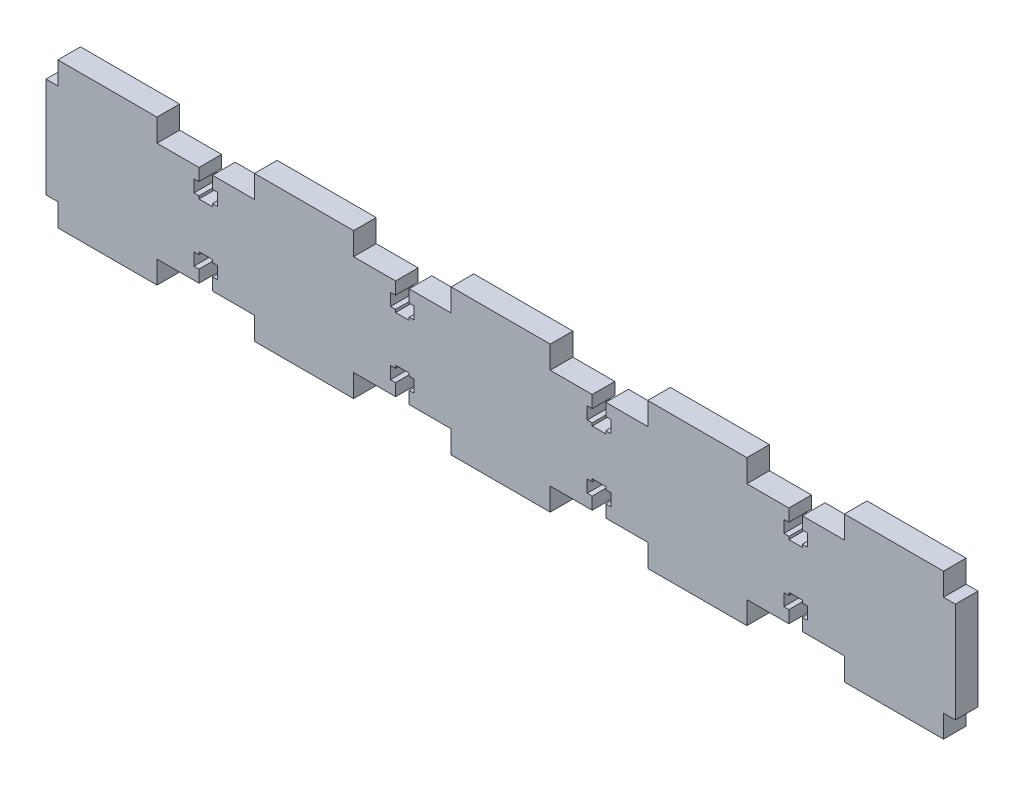
SolidWorks part; units mm, degrees
ref_plane "Front Plane" through (0, 0, 0) normal (0, 0, 1) x (1, 0, 0)
ref_plane "Top Plane" through (0, 0, 0) normal (0, 1, 0) x (1, 0, 0)
ref_plane "Right Plane" through (0, 0, 0) normal (1, 0, 0) x (0, 0, -1)
sketch "Sketch1" plane through (0, 0, 0) normal (0, 0, 1) x (1, 0, 0)
  line L0 (-38, 18.796) -> (-63.6, 18.796)
  line L1 (117.475, -12.954) -> (114.4, -12.954)
  line L2 (117.475, -12.954) -> (117.475, 12.954)
  line L3 (117.475, 12.954) -> (114.4, 12.954)
  line L4 (-117.475, -12.954) -> (-117.475, 12.954)
  line L5 (117.475, -12.954) -> (-117.475, 12.954) construction
  line L6 (117.475, 12.954) -> (-117.475, -12.954) construction
  line L7 (-88.8, 18.796) -> (-114.4, 18.796)
  line L8 (-88.8, 18.796) -> (-88.8, 12.954)
  line L9 (-63.6, 12.954) -> (-74.4474, 12.954)
  line L10 (-114.4, 18.796) -> (-114.4, 12.954)
  line L11 (-88.8, 18.796) -> (-114.4, 12.954) construction
  line L12 (-88.8, 12.954) -> (-114.4, 18.796) construction
  line L13 (-63.6, 18.796) -> (-63.6, 12.954)
  line L14 (-38, 18.796) -> (-38, 12.954)
  line L15 (12.8, 18.796) -> (-12.8, 18.796)
  line L16 (-12.8, 18.796) -> (-12.8, 12.954)
  line L17 (12.8, 18.796) -> (12.8, 12.954)
  line L18 (63.6, 18.796) -> (38, 18.796)
  line L19 (38, 18.796) -> (38, 12.954)
  line L20 (63.6, 18.796) -> (63.6, 12.954)
  line L21 (114.4, 18.796) -> (88.8, 18.796)
  line L22 (88.8, 18.796) -> (88.8, 12.954)
  line L23 (114.4, 18.796) -> (114.4, 12.954)
  line L24 (-114.4, 12.954) -> (-117.475, 12.954)
  line L25 (-12.8, 12.954) -> (-23.6474, 12.954)
  line L26 (38, 12.954) -> (27.1526, 12.954)
  line L27 (88.8, 12.954) -> (77.9526, 12.954)
  line L28 (-76.2, 12.954) -> (-76.2, -12.954) construction
  line L29 (-77.9526, 6.604) -> (-79.248, 6.604)
  line L30 (-77.9526, 9.779) -> (-79.248, 9.779)
  line L31 (-74.4474, 9.779) -> (-74.4474, 12.954)
  line L32 (-27.1526, 9.779) -> (-27.1526, 12.954)
  line L33 (-77.9526, 9.779) -> (-77.9526, 12.954)
  line L34 (-74.4474, 9.779) -> (-77.9526, 12.954) construction
  line L35 (-74.4474, 12.954) -> (-77.9526, 9.779) construction
  line L36 (-73.152, 6.604) -> (-74.4474, 6.604)
  line L37 (-73.152, 6.604) -> (-73.152, 9.779)
  line L38 (-73.152, 9.779) -> (-74.4474, 9.779)
  line L39 (-79.248, 6.604) -> (-79.248, 9.779)
  line L40 (-73.152, 6.604) -> (-79.248, 9.779) construction
  line L41 (-73.152, 9.779) -> (-79.248, 6.604) construction
  line L42 (-74.4474, 5.896) -> (-77.9526, 5.896)
  line L43 (-74.4474, 5.896) -> (-74.4474, 6.604)
  line L44 (-77.9526, 12.954) -> (-88.8, 12.954)
  line L45 (-77.9526, 5.896) -> (-77.9526, 6.604)
  line L46 (-74.4474, 5.896) -> (-77.9526, 6.604) construction
  line L47 (-74.4474, 6.604) -> (-77.9526, 5.896) construction
  line L48 (-23.6474, 9.779) -> (-23.6474, 12.954)
  line L49 (-27.1526, 9.779) -> (-28.448, 9.779)
  line L50 (-28.448, 6.604) -> (-28.448, 9.779)
  line L51 (-22.352, 9.779) -> (-23.6474, 9.779)
  line L52 (-22.352, 6.604) -> (-22.352, 9.779)
  line L53 (-22.352, 6.604) -> (-23.6474, 6.604)
  line L54 (-23.6474, 5.896) -> (-23.6474, 6.604)
  line L55 (-23.6474, 5.896) -> (-27.1526, 5.896)
  line L56 (-27.1526, 5.896) -> (-27.1526, 6.604)
  line L57 (-27.1526, 6.604) -> (-28.448, 6.604)
  line L58 (23.6474, 9.779) -> (23.6474, 12.954)
  line L59 (27.1526, 9.779) -> (27.1526, 12.954)
  line L60 (23.6474, 9.779) -> (22.352, 9.779)
  line L61 (22.352, 6.604) -> (22.352, 9.779)
  line L62 (28.448, 9.779) -> (27.1526, 9.779)
  line L63 (28.448, 6.604) -> (28.448, 9.779)
  line L64 (28.448, 6.604) -> (27.1526, 6.604)
  line L65 (27.1526, 5.896) -> (27.1526, 6.604)
  line L66 (27.1526, 5.896) -> (23.6474, 5.896)
  line L67 (23.6474, 5.896) -> (23.6474, 6.604)
  line L68 (23.6474, 6.604) -> (22.352, 6.604)
  line L69 (74.4474, 9.779) -> (74.4474, 12.954)
  line L70 (77.9526, 9.779) -> (77.9526, 12.954)
  line L71 (74.4474, 9.779) -> (73.152, 9.779)
  line L72 (73.152, 6.604) -> (73.152, 9.779)
  line L73 (79.248, 9.779) -> (77.9526, 9.779)
  line L74 (79.248, 6.604) -> (79.248, 9.779)
  line L75 (79.248, 6.604) -> (77.9526, 6.604)
  line L76 (77.9526, 5.896) -> (77.9526, 6.604)
  line L77 (77.9526, 5.896) -> (74.4474, 5.896)
  line L78 (74.4474, 5.896) -> (74.4474, 6.604)
  line L79 (74.4474, 6.604) -> (73.152, 6.604)
  line L80 (74.4474, 12.954) -> (63.6, 12.954)
  line L81 (23.6474, 12.954) -> (12.8, 12.954)
  line L82 (-27.1526, 12.954) -> (-38, 12.954)
  line L83 (117.475, 0) -> (-117.475, 0) construction
  line L84 (-74.4474, -6.604) -> (-77.9526, -5.896) construction
  line L85 (-74.4474, -5.896) -> (-77.9526, -6.604) construction
  line L86 (-73.152, -9.779) -> (-79.248, -6.604) construction
  line L87 (-73.152, -6.604) -> (-79.248, -9.779) construction
  line L88 (-74.4474, -12.954) -> (-77.9526, -9.779) construction
  line L89 (-74.4474, -9.779) -> (-77.9526, -12.954) construction
  line L90 (-88.8, -12.954) -> (-114.4, -18.796) construction
  line L91 (-88.8, -18.796) -> (-114.4, -12.954) construction
  line L92 (-27.1526, -12.954) -> (-38, -12.954)
  line L93 (23.6474, -12.954) -> (12.8, -12.954)
  line L94 (74.4474, -12.954) -> (63.6, -12.954)
  line L95 (74.4474, -6.604) -> (73.152, -6.604)
  line L96 (74.4474, -5.896) -> (74.4474, -6.604)
  line L97 (77.9526, -5.896) -> (74.4474, -5.896)
  line L98 (77.9526, -5.896) -> (77.9526, -6.604)
  line L99 (79.248, -6.604) -> (77.9526, -6.604)
  line L100 (79.248, -6.604) -> (79.248, -9.779)
  line L101 (79.248, -9.779) -> (77.9526, -9.779)
  line L102 (73.152, -6.604) -> (73.152, -9.779)
  line L103 (74.4474, -9.779) -> (73.152, -9.779)
  line L104 (77.9526, -9.779) -> (77.9526, -12.954)
  line L105 (74.4474, -9.779) -> (74.4474, -12.954)
  line L106 (23.6474, -6.604) -> (22.352, -6.604)
  line L107 (23.6474, -5.896) -> (23.6474, -6.604)
  line L108 (27.1526, -5.896) -> (23.6474, -5.896)
  line L109 (27.1526, -5.896) -> (27.1526, -6.604)
  line L110 (28.448, -6.604) -> (27.1526, -6.604)
  line L111 (28.448, -6.604) -> (28.448, -9.779)
  line L112 (28.448, -9.779) -> (27.1526, -9.779)
  line L113 (22.352, -6.604) -> (22.352, -9.779)
  line L114 (23.6474, -9.779) -> (22.352, -9.779)
  line L115 (27.1526, -9.779) -> (27.1526, -12.954)
  line L116 (23.6474, -9.779) -> (23.6474, -12.954)
  line L117 (-27.1526, -6.604) -> (-28.448, -6.604)
  line L118 (-27.1526, -5.896) -> (-27.1526, -6.604)
  line L119 (-23.6474, -5.896) -> (-27.1526, -5.896)
  line L120 (-23.6474, -5.896) -> (-23.6474, -6.604)
  line L121 (-22.352, -6.604) -> (-23.6474, -6.604)
  line L122 (-22.352, -6.604) -> (-22.352, -9.779)
  line L123 (-22.352, -9.779) -> (-23.6474, -9.779)
  line L124 (-28.448, -6.604) -> (-28.448, -9.779)
  line L125 (-27.1526, -9.779) -> (-28.448, -9.779)
  line L126 (-23.6474, -9.779) -> (-23.6474, -12.954)
  line L127 (-77.9526, -5.896) -> (-77.9526, -6.604)
  line L128 (-77.9526, -12.954) -> (-88.8, -12.954)
  line L129 (-74.4474, -5.896) -> (-74.4474, -6.604)
  line L130 (-74.4474, -5.896) -> (-77.9526, -5.896)
  line L131 (-79.248, -6.604) -> (-79.248, -9.779)
  line L132 (-73.152, -9.779) -> (-74.4474, -9.779)
  line L133 (-73.152, -6.604) -> (-73.152, -9.779)
  line L134 (-73.152, -6.604) -> (-74.4474, -6.604)
  line L135 (-77.9526, -9.779) -> (-77.9526, -12.954)
  line L136 (-27.1526, -9.779) -> (-27.1526, -12.954)
  line L137 (-74.4474, -9.779) -> (-74.4474, -12.954)
  line L138 (-77.9526, -9.779) -> (-79.248, -9.779)
  line L139 (-77.9526, -6.604) -> (-79.248, -6.604)
  line L140 (88.8, -12.954) -> (77.9526, -12.954)
  line L141 (38, -12.954) -> (27.1526, -12.954)
  line L142 (-12.8, -12.954) -> (-23.6474, -12.954)
  line L143 (-114.4, -12.954) -> (-117.475, -12.954)
  line L144 (114.4, -18.796) -> (114.4, -12.954)
  line L145 (88.8, -18.796) -> (88.8, -12.954)
  line L146 (114.4, -18.796) -> (88.8, -18.796)
  line L147 (63.6, -18.796) -> (63.6, -12.954)
  line L148 (38, -18.796) -> (38, -12.954)
  line L149 (63.6, -18.796) -> (38, -18.796)
  line L150 (12.8, -18.796) -> (12.8, -12.954)
  line L151 (-12.8, -18.796) -> (-12.8, -12.954)
  line L152 (12.8, -18.796) -> (-12.8, -18.796)
  line L153 (-38, -18.796) -> (-38, -12.954)
  line L154 (-63.6, -18.796) -> (-63.6, -12.954)
  line L155 (-114.4, -18.796) -> (-114.4, -12.954)
  line L156 (-63.6, -12.954) -> (-74.4474, -12.954)
  line L157 (-88.8, -18.796) -> (-88.8, -12.954)
  line L158 (-88.8, -18.796) -> (-114.4, -18.796)
  line L159 (117.475, -12.954) -> (114.4, -12.954)
  line L160 (-38, -18.796) -> (-63.6, -18.796)
  line L161 (-114.4, -12.954) -> (-117.475, -12.954)
  line L162 (-77.9526, -12.954) -> (-88.8, -12.954)
  line L163 (-63.6, -12.954) -> (-74.4474, -12.954)
  line L164 (-27.1526, -12.954) -> (-38, -12.954)
  line L165 (-12.8, -12.954) -> (-23.6474, -12.954)
  line L166 (23.6474, -12.954) -> (12.8, -12.954)
  line L167 (38, -12.954) -> (27.1526, -12.954)
  line L168 (74.4474, -12.954) -> (63.6, -12.954)
  line L169 (88.8, -12.954) -> (77.9526, -12.954)
  point P0 (0, 0)
  point P6 (-101.6, 15.875)
  point P29 (-76.2, 11.3665)
  point P34 (-76.2, 8.1915)
  point P39 (-76.2, 6.25)
  point P150 (-76.2, -6.25)
  point P151 (-76.2, -8.1915)
  point P152 (-76.2, -11.3665)
  point P153 (-101.6, -15.875)
  dimension "D1" = 234.95
  dimension "D2" = 25.908
  dimension "D3" = 25.6
  dimension "D4" = 5.842
  dimension "D5" = 15.875
  dimension "D7" = 3.175
  dimension "D8" = 3.5052
  dimension "D9" = 3.175
  dimension "D10" = 6.096
  dimension "D11" = 0.708
  dimension "D6" = 5
  dimension "D12" = 4
extrude "Boss-Extrude1" add sketch "Sketch1" along normal blind 5.842 contours L160 L153 L92 L136 L125 L124 L117 L118 L119 L120 L121 L122 L123 L126 L142 L151 L152 L150 L93 L116 L114 L113 L106 L107 L108 L109 L110 L111 L112 L115 L141 L148 L149 L147 L94 L105 L103 L102 L95 L96 L97 L98 L99 L100 L101 L104 L140 L145 L146 L144 L1
